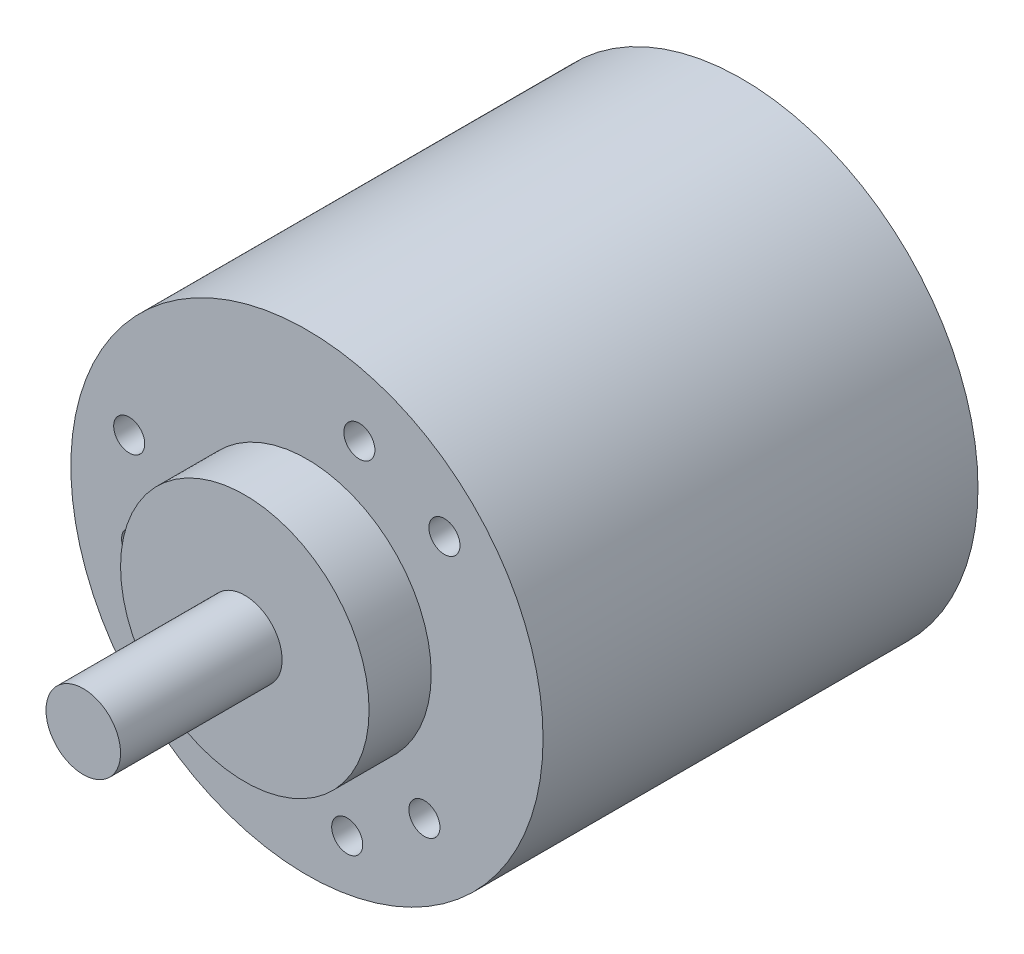
SolidWorks part; units mm, degrees
ref_plane "Plan de face" through (0, 0, 0) normal (0, 0, 1) x (1, 0, 0)
ref_plane "Plan de dessus" through (0, 0, 0) normal (0, 1, 0) x (1, 0, 0)
ref_plane "Plan de droite" through (0, 0, 0) normal (1, 0, 0) x (0, 0, -1)
sketch "Esquisse1" plane through (0, 0, 0) normal (0, 0, 1) x (1, 0, 0)
  circle A0 centre (0, 0) radius 19
  dimension "D1" = 38
extrude "Boss.-Extru.1" add sketch "Esquisse1" along normal blind 35
sketch "Esquisse2" plane through (0, 0, 35) normal (0, 0, 1) x (1, 0, 0)
  circle A0 centre (0, 0) radius 10
extrude "Boss.-Extru.2" add sketch "Esquisse2" along normal blind 5
sketch "Esquisse3" plane through (0, 0, 40) normal (0, 0, 1) x (1, 0, 0)
  circle A0 centre (0, 0) radius 3
  dimension "D1" = 6
extrude "Boss.-Extru.3" add sketch "Esquisse3" along normal blind 13
sketch "Esquisse4" plane through (0, 0, 35) normal (0, 0, 1) x (1, 0, 0)
  line L0 (0, 0) -> (3.2395, -14.646)
  line L1 (0, 0) -> (9.4533, -10.3264)
  line L2 (0, 0) -> (-13.6696, -3.0236)
  line L3 (-14.3036, 4.5175) -> (0, 0)
  line L4 (4.2163, 13.35) -> (0, 0)
  line L5 (11.064, 10.1285) -> (0, 0)
  circle A0 centre (11.064, 10.1285) radius 1.25
  circle A1 centre (-13.6696, -3.0236) radius 1.25
  circle A2 centre (-14.3036, 4.5175) radius 1.25
  circle A3 centre (3.2395, -14.646) radius 1.25
  circle A4 centre (9.4533, -10.3264) radius 1.25
  circle A5 centre (4.2163, 13.35) radius 1.25
  dimension "D1" = 2.5
  dimension "D2" = 2.5
  dimension "D3" = 2.5
  dimension "D4" = 2.5
  dimension "D5" = 2.5
  dimension "D6" = 2.5
  dimension "D7" = 30
  dimension "D8" = 30
  dimension "D12" = 30
  dimension "D14" = 14
  dimension "D9" = 15
  dimension "D10" = 15
  dimension "D11" = 14
  dimension "D13" = 14
  dimension "D15" = 120
  dimension "D16" = 120
extrude "Enlèv. mat.-Extru.1" cut sketch "Esquisse4" against normal blind 8
